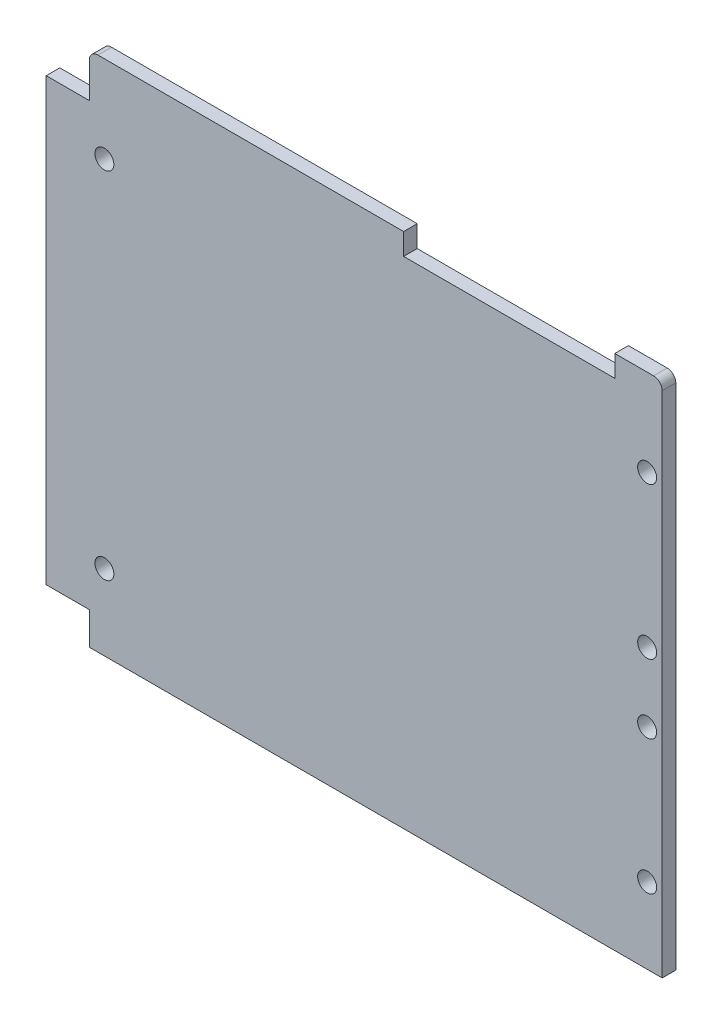
SolidWorks part; units mm, degrees
ref_plane "Front Plane" through (0, 0, 0) normal (0, 0, 1) x (1, 0, 0)
ref_plane "Top Plane" through (0, 0, 0) normal (0, 1, 0) x (1, 0, 0)
ref_plane "Right Plane" through (0, 0, 0) normal (1, 0, 0) x (0, 0, -1)
sketch "BPR2 PCB Outline" plane through (0, 0, 0) normal (0, 0, 1) x (1, 0, 0)
  line L0 (114.543, 6.6204) -> (102.643, 6.6204)
  line L1 (50.073, 67.1204) -> (114.543, 67.1204)
  line L2 (49.073, 66.1204) -> (49.073, 6.6204)
  line L3 (49.073, 6.6204) -> (82.643, 6.6204)
  line L4 (115.543, 66.1204) -> (115.543, 7.6204)
  line L9 (82.643, 6.6204) -> (102.643, 6.6204)
  arc A0 (114.543, 6.6204) -> (115.543, 7.6204) centre (114.543, 7.6204) ccw
  arc A1 (114.543, 67.1204) -> (115.543, 66.1204) centre (114.543, 66.1204) cw
  arc A2 (50.073, 67.1204) -> (49.073, 66.1204) centre (50.073, 66.1204) ccw
  point P6 (115.543, 6.6204)
  point P9 (115.543, 67.1204)
  point P12 (49.073, 67.1204)
  dimension "D2" = 66.47
  dimension "D4" = 11.9
  dimension "D3" = 1
  dimension "D1" = 60.5
sketch "23" plane through (0, 0, 0) normal (0, 0, 1) x (1, 0, 0)
  point P0 (0, 0)
extrude "Boss-Extrude1" add sketch "BPR2 PCB Outline" against normal blind 1.5748
sketch "Sketch3" plane through (0, 0, 0) normal (0, 0, 1) x (1, 0, 0)
  line L0 (115.543, 7.6204) -> (115.543, 66.1204) construction
  line L1 (49.073, 6.6204) -> (115.543, 6.6204)
  line L2 (49.073, 6.6204) -> (49.073, 11.9564)
  line L3 (49.073, 11.9564) -> (115.543, 11.9564)
  line L4 (115.543, 6.6204) -> (115.543, 11.9564)
extrude "Boss-Extrude2" add sketch "Sketch3" against normal blind 1.575
sketch "Sketch4" plane through (0, 0, 0) normal (0, 0, 1) x (1, 0, 0)
  line L1 (49.073, 6.6204) -> (115.543, 6.6204)
  line L2 (49.073, 6.6204) -> (49.073, 7.1204)
  line L3 (49.073, 7.1204) -> (115.543, 7.1204)
  line L4 (115.543, 6.6204) -> (115.543, 7.1204)
  dimension "D1" = 0.5
extrude "Cut-Extrude1" cut sketch "Sketch4" against normal through all
hole_wizard "M2 Clearance Hole1" positions "Sketch1" profile "Sketch2" hole size "M2" standard "ISO" end condition through all
sketch "Sketch1" plane through (32.7629, 104.0075, -6.5748) normal (0, 0, -1) x (1, 0, 0)
  point P0 (18.0601, 88.112)
  point P3 (18.0601, 46.962)
  point P6 (81.0301, 46.962)
  point P9 (81.0301, 64.537)
  point P12 (81.0301, 88.112)
  point P15 (81.0301, 72.537)
sketch "Sketch2" plane through (50.823, 15.8954, -6.5748) normal (1, 0, 0) x (0, 1, 0)
  line L0 (0, 0) -> (0, 6.5748)
  line L1 (0, 6.5748) -> (1.1, 6.5748)
  line L2 (1.1, 6.5748) -> (1.1, 0)
  line L3 (1.1, 0) -> (0, 0)
  line L4 (0, -6.35) -> (0, 107.95) construction
  dimension "Thru Hole Dia." = 2.2
  dimension "Thru Hole Depth" = 6.5748
sketch "Sketch5" plane through (0, 0, 0) normal (0, 0, 1) x (1, 0, 0)
  line L0 (-957.9863, 62.0454) -> (49042.0137, 62.0454) construction
  line L1 (43.404, 10.8954) -> (50043.404, 10.8954) construction
  line L2 (44.073, -936.3675) -> (44.073, 49063.6325) construction
  line L3 (49.073, 66.1204) -> (49.073, 7.1204) construction
  line L4 (49.073, -937.9546) -> (49.073, 49062.0454) construction
  line L6 (49.073, 62.0454) -> (44.073, 62.0454)
  line L7 (49.073, 62.0454) -> (49.073, 10.8954)
  line L8 (49.073, 10.8954) -> (44.073, 10.8954)
  line L9 (44.073, 62.0454) -> (44.073, 10.8954)
  dimension "D1" = 5
  dimension "D2" = 5
  dimension "D3" = 5
extrude "Boss-Extrude3" add sketch "Sketch5" against normal blind 1.575
sketch "Sketch6" plane through (0, 0, 0) normal (0, 0, 1) x (1, 0, 0)
  line L0 (110.043, -921.7746) -> (110.043, 49078.2254) construction
  line L1 (-911.3722, 64.6204) -> (49088.6278, 64.6204) construction
  line L2 (115.543, 7.1204) -> (115.543, 66.1204) construction
  line L3 (114.543, 67.1204) -> (50.073, 67.1204) construction
  line L4 (85.543, -929.0289) -> (85.543, 49070.9711) construction
  line L5 (-930.8966, 67.1204) -> (49069.1034, 67.1204) construction
  line L7 (85.543, 64.6204) -> (110.043, 64.6204)
  line L8 (85.543, 64.6204) -> (85.543, 67.1204)
  line L9 (85.543, 67.1204) -> (110.043, 67.1204)
  line L10 (110.043, 64.6204) -> (110.043, 67.1204)
  dimension "D1" = 5.5
  dimension "D2" = 2.5
  dimension "D3" = 30
extrude "Cut-Extrude2" cut sketch "Sketch6" against normal through all
